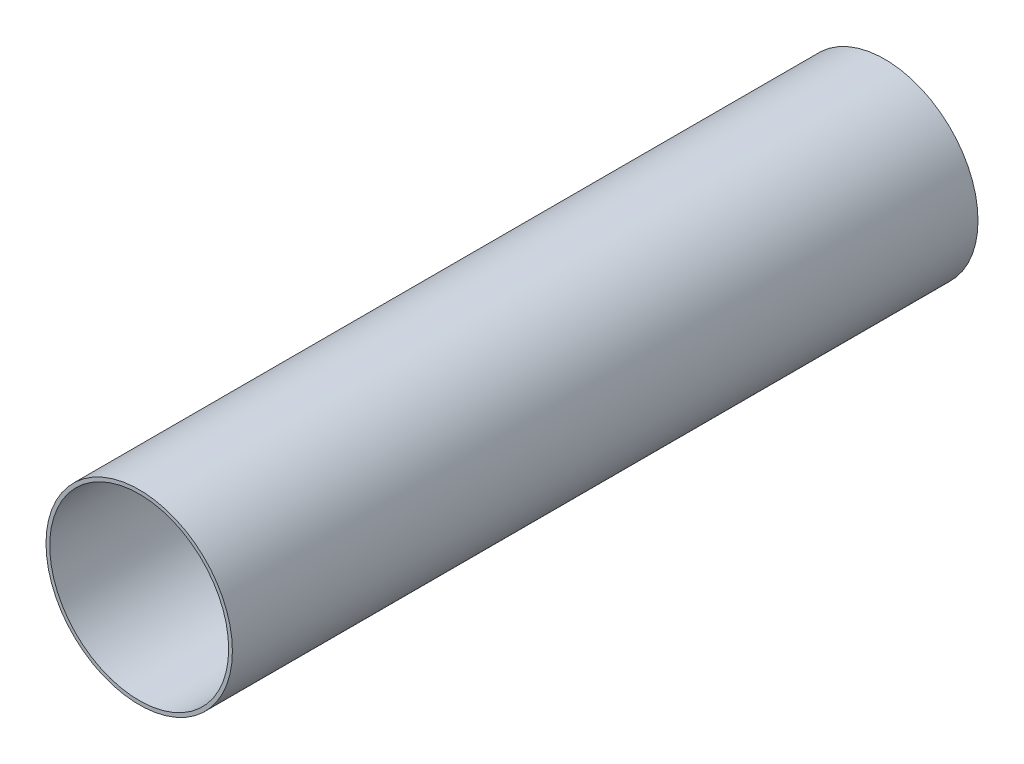
SolidWorks part; units mm, degrees
ref_plane "Plan de face" through (0, 0, 0) normal (0, 0, 1) x (1, 0, 0)
ref_plane "Plan de dessus" through (0, 0, 0) normal (0, 1, 0) x (1, 0, 0)
ref_plane "Plan de droite" through (0, 0, 0) normal (1, 0, 0) x (0, 0, -1)
sketch "Esquisse1" plane through (0, 0, 0) normal (0, 0, 1) x (1, 0, 0)
  circle A0 centre (0, 0) radius 25
  dimension "D1" = 50
extrude "Extru.-Mince1" add sketch "Esquisse1" along normal blind 200 thin thin type one direction reverse wall 1
